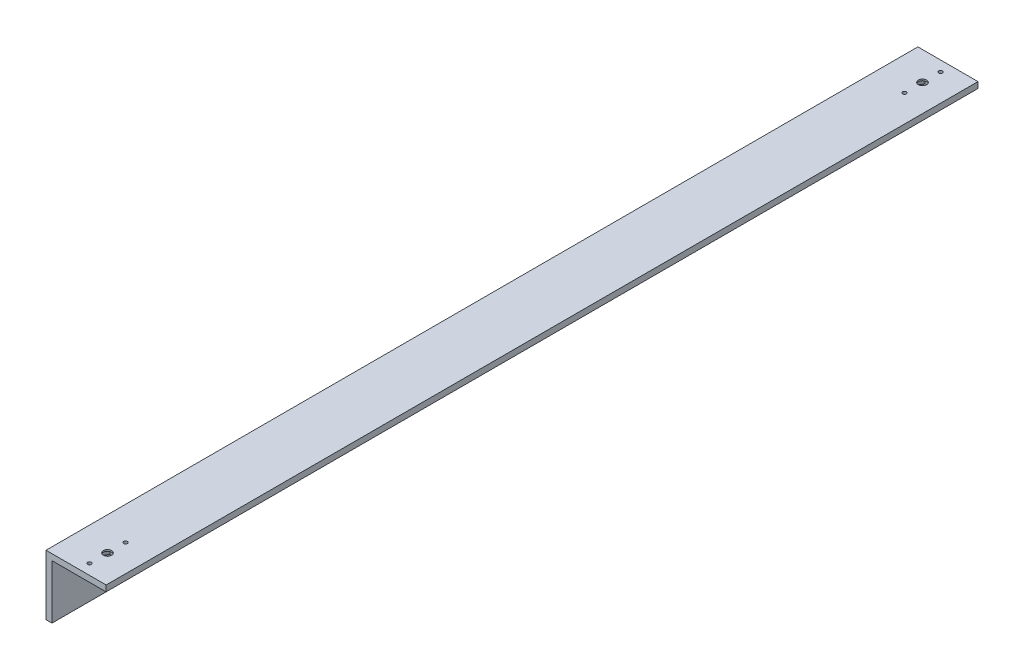
SolidWorks part; units mm, degrees
ref_plane "Front Plane" through (0, 0, 0) normal (0, 0, 1) x (1, 0, 0)
ref_plane "Top Plane" through (0, 0, 0) normal (0, 1, 0) x (1, 0, 0)
ref_plane "Right Plane" through (0, 0, 0) normal (1, 0, 0) x (0, 0, -1)
sketch "Sketch1" plane through (0, 0, 0) normal (0, 0, 1) x (1, 0, 0)
  line L0 (0, 0) -> (0, 40)
  line L1 (0, 40) -> (40, 40)
  line L2 (40, 40) -> (40, 36)
  line L3 (40, 36) -> (4, 36)
  line L4 (4, 36) -> (4, 0)
  line L5 (4, 0) -> (0, 0)
  dimension "D1" = 4
  dimension "D2" = 4
  dimension "D3" = 40
  dimension "D4" = 40
extrude "Boss-Extrude1" add sketch "Sketch1" along normal blind 580
sketch "Sketch2" plane through (0, 36, 0) normal (0, 1, 0) x (1, 0, 0)
  line L0 (40, 0) -> (0, 0) construction
  line L1 (24.3094, -14.9243) -> (19.6906, -14.9243)
  line L2 (19.6906, -14.9243) -> (17.3812, -18.9243)
  line L3 (17.3812, -18.9243) -> (19.6906, -22.9243)
  line L4 (19.6906, -22.9243) -> (24.3094, -22.9243)
  line L5 (24.3094, -22.9243) -> (26.6188, -18.9243)
  line L6 (26.6188, -18.9243) -> (24.3094, -14.9243)
  line L13 (40, -580) -> (0, -580) construction
  line L14 (24.3094, -557.0757) -> (19.6906, -557.0757)
  line L15 (19.6906, -557.0757) -> (17.3812, -561.0757)
  line L16 (17.3812, -561.0757) -> (19.6906, -565.0757)
  line L17 (19.6906, -565.0757) -> (24.3094, -565.0757)
  line L18 (24.3094, -565.0757) -> (26.6188, -561.0757)
  line L19 (26.6188, -561.0757) -> (24.3094, -557.0757)
  circle A0 centre (22, -18.9243) radius 4 construction
  circle A1 centre (22, -561.0757) radius 4 construction
  point P21 (22, -561.0757)
  point P22 (22, -18.9243)
  dimension "D1" = 8
  dimension "D2" = 8
extrude "Cut-Extrude1" cut sketch "Sketch2" along normal blind 3
sketch "Sketch3" plane through (0, 40, 0) normal (0, 1, 0) x (1, 0, 0)
  line L0 (22, -30.9243) -> (22, -6.9243) construction
  line L1 (22, -18.9243) -> (8.726, -18.9243) construction
  line L2 (40, -290) -> (72.8155, -290) construction
  line L3 (40, -580) -> (40, 0) construction
  line L4 (22, -561.0757) -> (8.726, -561.0757) construction
  line L5 (22, -549.0757) -> (22, -573.0757) construction
  point P4 (22, -6.9243)
  point P6 (22, -30.9243)
  point P15 (22, -549.0757)
  point P16 (22, -573.0757)
  dimension "D1" = 12
hole_wizard "Tap Drill for M3 Tap1" positions "Sketch4" profile "Sketch5" hole size "M3" standard "ISO" end condition through all
sketch "Sketch4" plane through (0, 40, 0) normal (0, 1, 0) x (1, 0, 0)
  point P0 (22, -549.0757)
  point P3 (22, -573.0757)
  point P6 (22, -30.9243)
  point P9 (22, -6.9243)
sketch "Sketch5" plane through (22, 40, 549.0757) normal (1, 0, 0) x (0, 0, 1)
  line L0 (0, 0) -> (0, 40)
  line L1 (0, 40) -> (1.25, 40)
  line L2 (1.25, 40) -> (1.25, 0)
  line L5 (1.25, 0) -> (0, 0)
  line L11 (0, -6.35) -> (0, 107.95) construction
  dimension "Thru Hole Dia." = 2.5
  dimension "Thru Hole Depth" = 40
hole_wizard "M5 Clearance Hole1" positions "Sketch6" profile "Sketch7" hole size "M5" standard "ISO" end condition through all
sketch "Sketch6" plane through (0, 39, 0) normal (0, -1, 0) x (-1, 0, 0)
  point P0 (-22, -561.0757)
  point P3 (-22, -18.9243)
sketch "Sketch7" plane through (22, 39, 561.0757) normal (1, 0, 0) x (0, 0, -1)
  line L0 (0, 0) -> (0, 1)
  line L1 (0, 1) -> (2.75, 1)
  line L2 (2.75, 1) -> (2.75, 0)
  line L5 (2.75, 0) -> (0, 0)
  line L11 (0, -6.35) -> (0, 107.95) construction
  dimension "Thru Hole Dia." = 5.5
  dimension "Thru Hole Depth" = 1
